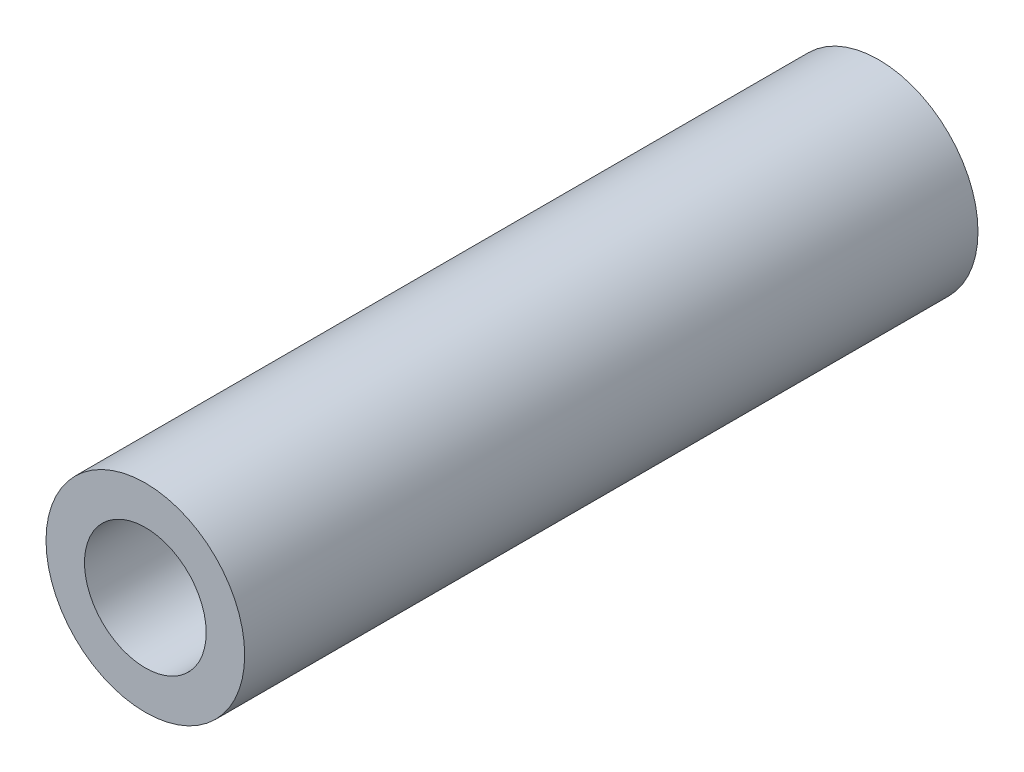
SolidWorks part; units mm, degrees
ref_plane "Front Plane" through (0, 0, 0) normal (0, 0, 1) x (1, 0, 0)
ref_plane "Top Plane" through (0, 0, 0) normal (0, 1, 0) x (1, 0, 0)
ref_plane "Right Plane" through (0, 0, 0) normal (1, 0, 0) x (0, 0, -1)
sketch "Sketch1" plane through (0, 0, 0) normal (0, 0, 1) x (1, 0, 0)
  circle A0 centre (0, 0) radius 2.4892
  circle A1 centre (0, 0) radius 4.064
  dimension "D1" = 4.9784
  dimension "D2" = 8.128
extrude "Boss-Extrude1" add sketch "Sketch1" along normal mid plane 30
